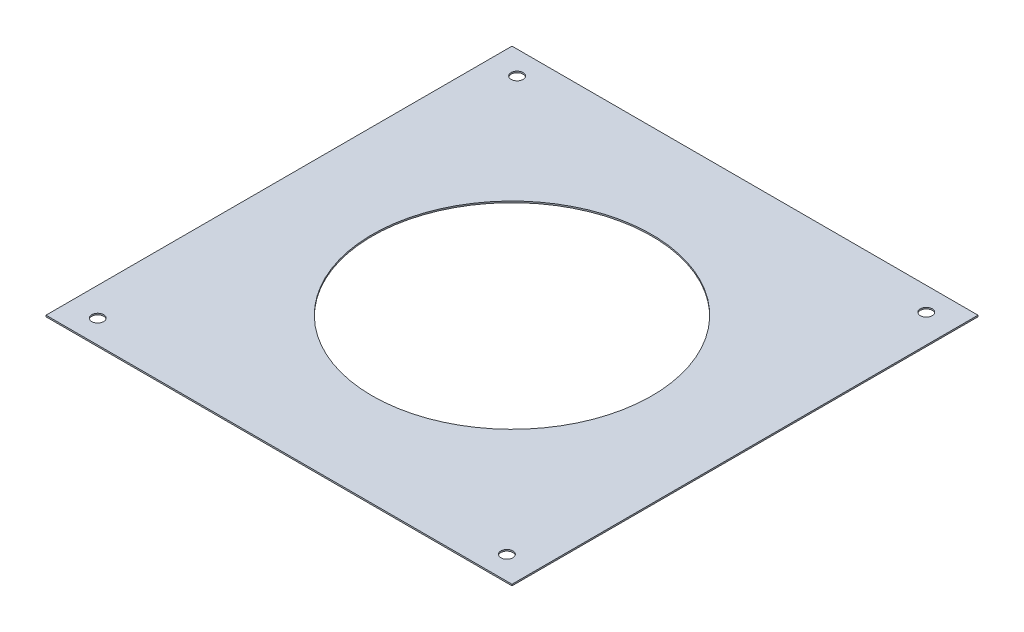
SolidWorks part; units mm, degrees
ref_plane "Front Plane" through (0, 0, 0) normal (0, 0, 1) x (1, 0, 0)
ref_plane "Top Plane" through (0, 0, 0) normal (0, 1, 0) x (1, 0, 0)
ref_plane "Right Plane" through (0, 0, 0) normal (1, 0, 0) x (0, 0, -1)
sketch "Sketch1" plane through (0, 0, 0) normal (0, 1, 0) x (1, 0, 0)
  line L0 (127, 254) -> (127, 241.3) construction
  line L1 (0, 0) -> (254, 0)
  line L2 (0, 0) -> (0, 254)
  line L3 (0, 254) -> (254, 254)
  line L4 (254, 0) -> (254, 254)
  line L5 (15.494, 12.7) -> (238.506, 12.7) construction
  line L6 (15.494, 12.7) -> (15.494, 241.3) construction
  line L7 (15.494, 241.3) -> (238.506, 241.3) construction
  line L8 (238.506, 12.7) -> (238.506, 241.3) construction
  line L9 (238.506, 127) -> (254, 127) construction
  circle A0 centre (15.494, 241.3) radius 3.2639
  circle A1 centre (238.506, 241.3) radius 3.2639
  circle A2 centre (238.506, 12.7) radius 3.2639
  circle A3 centre (15.494, 12.7) radius 3.2639
  circle A4 centre (127, 127) radius 76.2
  dimension "D2" = 12.7
  dimension "D4" = 6.5278
  dimension "D5" = 152.4
  dimension "D1" = 254
  dimension "D3" = 15.494
extrude "Boss-Extrude1" add sketch "Sketch1" along normal blind 0.7937
